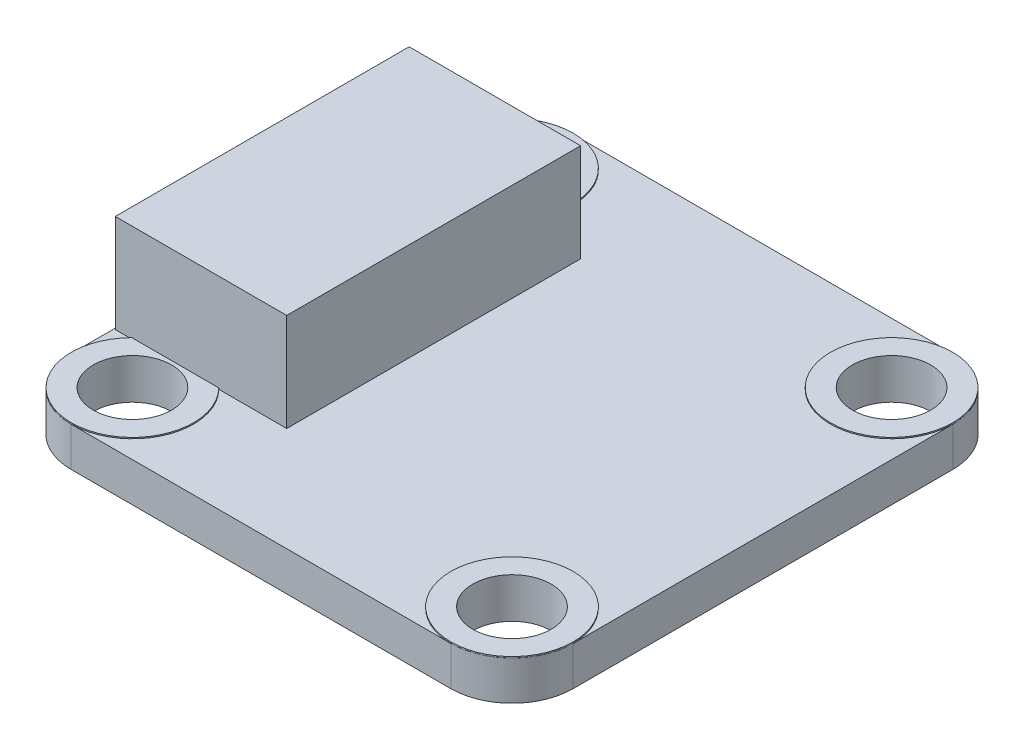
SolidWorks part; units mm, degrees
ref_plane "Front Plane" through (0, 0, 0) normal (0, 0, 1) x (1, 0, 0)
ref_plane "Top Plane" through (0, 0, 0) normal (0, 1, 0) x (1, 0, 0)
ref_plane "Right Plane" through (0, 0, 0) normal (1, 0, 0) x (0, 0, -1)
sketch "Sketch1" plane through (0, 0, 0) normal (0, 1, 0) x (1, 0, 0)
  line L1 (7.75, -10.25) -> (-7.75, -10.25)
  line L2 (10.25, -7.75) -> (10.25, 7.75)
  line L3 (7.75, 10.25) -> (-7.75, 10.25)
  line L4 (-10.25, -7.75) -> (-10.25, 7.75)
  line L5 (10.25, -10.25) -> (-10.25, 10.25) construction
  line L6 (10.25, 10.25) -> (-10.25, -10.25) construction
  arc A0 (-7.75, -10.25) -> (-10.25, -7.75) centre (-7.75, -7.75) cw
  arc A1 (7.75, -10.25) -> (10.25, -7.75) centre (7.75, -7.75) ccw
  arc A2 (10.25, 7.75) -> (7.75, 10.25) centre (7.75, 7.75) ccw
  arc A3 (-7.75, 10.25) -> (-10.25, 7.75) centre (-7.75, 7.75) ccw
  point P0 (0, 0)
  dimension "D2" = 2.5
  dimension "D1" = 20.5
extrude "Boss-Extrude1" add sketch "Sketch1" along normal blind 1.6
sketch "Sketch2" plane through (0, 1.6, 0) normal (0, 1, 0) x (1, 0, 0)
  line L1 (7.75, -7.75) -> (-7.75, -7.75) construction
  line L2 (7.75, -7.75) -> (7.75, 7.75) construction
  line L3 (7.75, 7.75) -> (-7.75, 7.75) construction
  line L4 (-7.75, -7.75) -> (-7.75, 7.75) construction
  line L5 (7.75, -7.75) -> (-7.75, 7.75) construction
  line L6 (7.75, 7.75) -> (-7.75, -7.75) construction
  circle A0 centre (-7.75, 7.75) radius 2.495
  circle A1 centre (7.75, 7.75) radius 2.495
  circle A2 centre (7.75, -7.75) radius 2.495
  circle A3 centre (-7.75, -7.75) radius 2.495
  point P0 (0, 0)
  point P7 (0, 0)
  point P8 (0, 0)
  point P10 (0, 0)
  point P13 (0, 0)
  point P16 (0, 0)
  point P19 (0, 0)
  dimension "D2" = 4.99
  dimension "D1" = 15.5
  dimension "D3" = 4
extrude "Boss-Extrude2" add sketch "Sketch2" along normal blind 0.05
sketch "Sketch3" plane through (0, 1.65, 0) normal (0, 1, 0) x (1, 0, 0)
  circle A0 centre (-7.75, 7.75) radius 1.6
  circle A1 centre (7.75, 7.75) radius 1.6
  circle A2 centre (7.75, -7.75) radius 1.6
  circle A3 centre (-7.75, -7.75) radius 1.6
  point P3 (0, 0)
  point P12 (0, 0)
  dimension "D1" = 3.2
  dimension "D2" = 4
extrude "Cut-Extrude1" cut sketch "Sketch3" against normal through all
sketch "Sketch4" plane through (0, 1.6, 0) normal (0, 1, 0) x (1, 0, 0)
  line L1 (-3.2, -6) -> (-10.2, -6)
  line L2 (-3.2, -6) -> (-3.2, 6)
  line L3 (-3.2, 6) -> (-10.2, 6)
  line L4 (-10.2, -6) -> (-10.2, 6)
  line L5 (-3.2, -6) -> (-10.2, 6) construction
  line L6 (-3.2, 6) -> (-10.2, -6) construction
  line L7 (-10.25, 7.75) -> (-10.25, -7.75) construction
  point P0 (-6.7, 0)
  point P7 (0, 0)
  dimension "D1" = 7
  dimension "D2" = 12
  dimension "D3" = 0.05
extrude "Boss-Extrude3" add sketch "Sketch4" along normal blind 4
